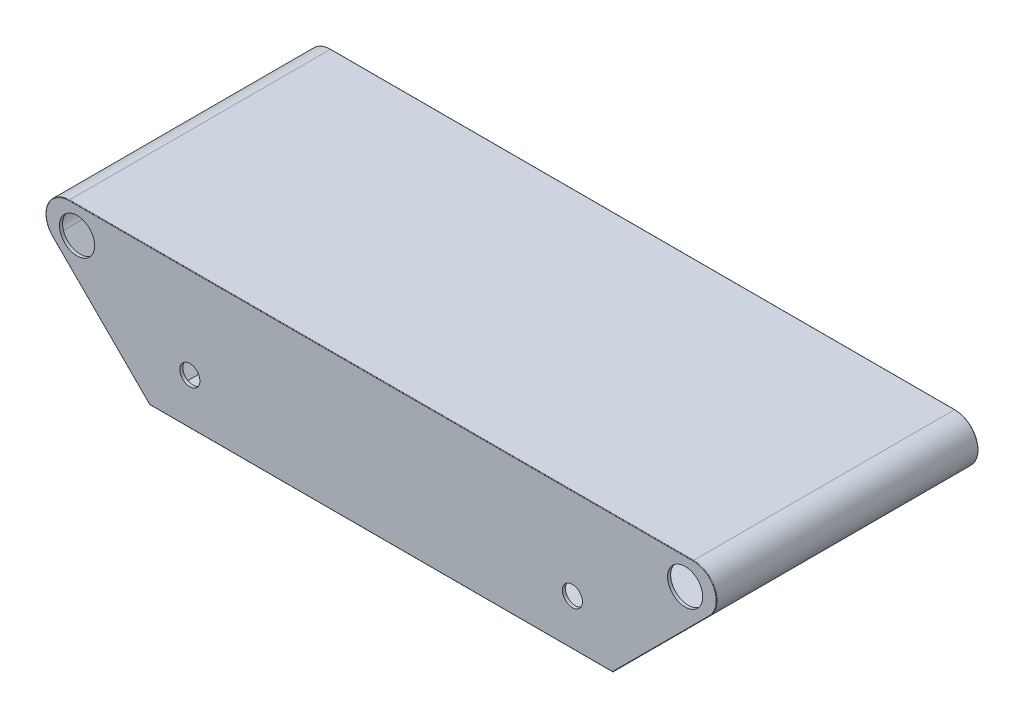
SolidWorks part; units mm, degrees
material "AISI 316 Stainless Steel Sheet (SS)"
ref_plane "Alzado" through (0, 0, 0) normal (0, 0, 1) x (1, 0, 0)
ref_plane "Planta" through (0, 0, 0) normal (0, 1, 0) x (1, 0, 0)
ref_plane "Vista lateral" through (0, 0, 0) normal (1, 0, 0) x (0, 0, -1)
sketch "Sketch1" plane through (0, 0, 0) normal (0, 1, 0) x (1, 0, 0)
  line L1 (-230, -130) -> (230, -130)
  line L2 (-230, -130) -> (-230, 130)
  line L3 (-230, 130) -> (230, 130)
  line L4 (230, -130) -> (230, 130)
  line L5 (-230, -130) -> (230, 130) construction
  line L6 (-230, 130) -> (230, -130) construction
  point P0 (0, 0)
  dimension "D1" = 460
  dimension "D2" = 260
extrude "Boss-Extrude1" add sketch "Sketch1" along normal blind 3.04
ref_plane "Plane1" through (0, 0, 130) normal (0, 0, 1) x (1, 0, 0)
sketch "Sketch2" plane through (0, 0, 130) normal (0, 0, 1) x (1, 0, 0)
  line L0 (-230, 0) -> (230, 0)
  line L8 (230, 0) -> (326.402, 96.402)
  line L9 (310, 136) -> (-310, 136)
  line L10 (-326.402, 96.402) -> (-230, 0)
  line L11 (-230, 0) -> (-230, 136) construction
  line L12 (230, 0) -> (230, 136) construction
  arc A0 (326.402, 96.402) -> (310, 136) centre (310, 112.804) ccw
  arc A1 (-310, 136) -> (-326.402, 96.402) centre (-310, 112.804) ccw
  dimension "D3" = 620
  dimension "D4" = 112.804
  dimension "D1" = 45
  dimension "D2" = 136
  dimension "D5" = 310
extrude "Boss-Extrude2" add sketch "Sketch2" against normal blind 3.04
mirror "Mirror1" about plane through (0, 0, 0) normal (0, 0, 1) of "Boss-Extrude2"
sketch "Sketch4" plane through (0, 0, -130) normal (0, 0, -1) x (-1, 0, 0)
  line L4 (-324.2524, 98.5516) -> (-228.7408, 3.04)
  line L5 (-228.7408, 3.04) -> (228.7408, 3.04)
  line L6 (228.7408, 3.04) -> (324.2524, 98.5516)
  line L7 (310, 132.96) -> (-310, 132.96)
  line L8 (-326.402, 96.402) -> (-230, 0)
  line L9 (-230, 0) -> (230, 0)
  line L10 (230, 0) -> (326.402, 96.402)
  line L11 (310, 136) -> (-310, 136)
  line L12 (-326.402, 96.402) -> (-230, 0)
  line L13 (-230, 0) -> (230, 0)
  line L14 (230, 0) -> (326.402, 96.402)
  line L15 (310, 136) -> (-310, 136)
  line L16 (-287.7494, 136) -> (-287.7494, 132.96)
  arc A2 (324.2524, 98.5516) -> (310, 132.96) centre (310, 112.804) ccw
  arc A3 (-310, 132.96) -> (-324.2524, 98.5516) centre (-310, 112.804) ccw
  arc A4 (326.402, 96.402) -> (310, 136) centre (310, 112.804) ccw
  arc A5 (-310, 136) -> (-326.402, 96.402) centre (-310, 112.804) ccw
  arc A6 (326.402, 96.402) -> (310, 136) centre (310, 112.804) ccw
  arc A7 (-310, 136) -> (-326.402, 96.402) centre (-310, 112.804) ccw
  dimension "D1" = 0
  dimension "D2" = 3.04
extrude "Boss-Extrude4" add sketch "Sketch4" against normal up to surface (260 mm away) contours L15 A7 L12 L13 L14 A6 | L7 A3 L4 L5 L6 A2 up to face at (0, 79.2939, 130)
sketch "Sketch6" plane through (0, 0, -130) normal (0, 0, -1) x (-1, 0, 0)
  line L0 (-310, 136) -> (310, 136) construction
  line L1 (-230, 0) -> (-326.402, 96.402) construction
  line L2 (0, 74.8) -> (0, -74.8) construction
  circle A5 centre (-302.0233, 109.5) radius 17.465
  circle A7 centre (302.0233, 109.5) radius 17.465
  point P7 (-312.5549, 88.9433)
  point P11 (0, 0)
  dimension "D1" = 26.5
  dimension "D3" = 26.5
  dimension "D2" = 34.93
fillet "Fillet1" radius 0.5 14 edges at (-278.201, 48.201, 130) (-331.4303, 121.6807, 130) (0, 136, 130) (331.4303, 121.6807, 130) (-278.201, 48.201, -130) (-331.4303, 121.6807, -130) (0, 136, -130) (331.4303, 121.6807, -130) (278.201, 48.201, 130) (0, 0, 130) (-230, 0, 0) (0, 0, -130) (278.201, 48.201, -130) (230, 0, 0)
extrude "Cut-Extrude1" cut sketch "Sketch6" against normal through all contours A5 | A7
sketch "Sketch8" plane through (0, 0, 130) normal (0, 0, 1) x (1, 0, 0)
  line L0 (-190, 45.5) -> (0, 45.5) construction
  line L1 (-229.7929, 0.5) -> (229.7929, 0.5) construction
  line L2 (0, -74.8) -> (0, 74.8) construction
  circle A0 centre (-190, 45.5) radius 10
  circle A1 centre (190, 45.5) radius 10
  dimension "D3" = 20
  dimension "D1" = 45
  dimension "D2" = 190
extrude "Cut-Extrude2" cut sketch "Sketch8" against normal through all
